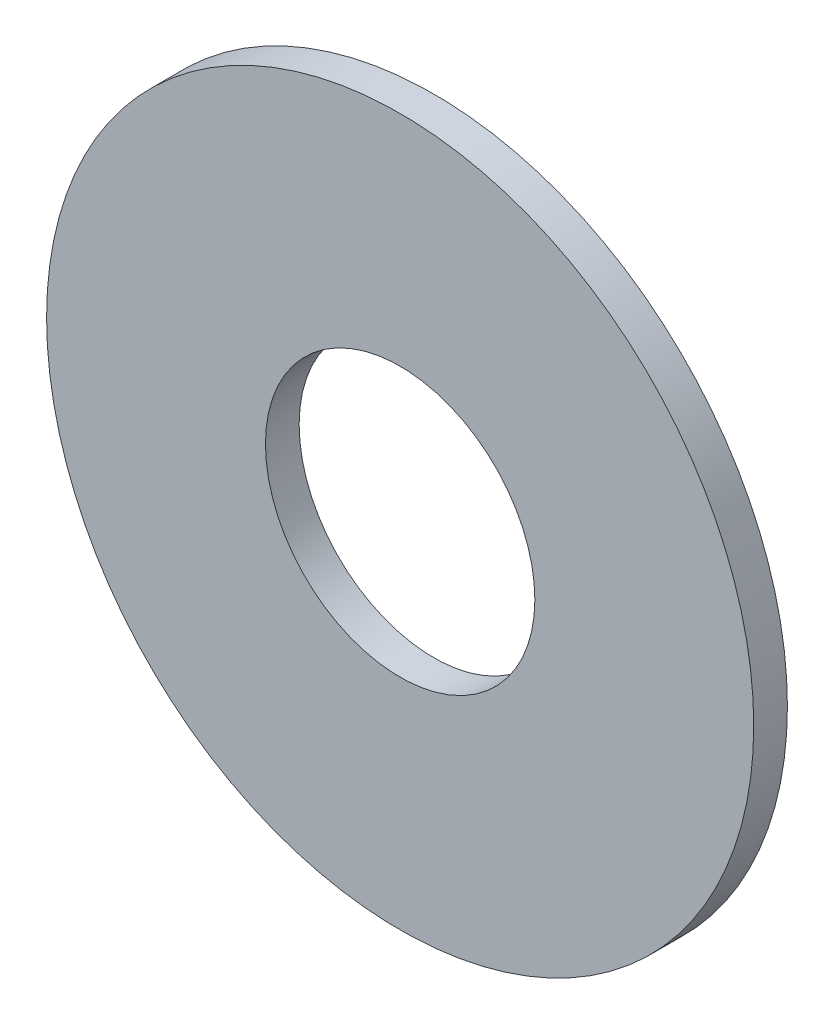
SolidWorks part; units mm, degrees
ref_plane "Alzado" through (0, 0, 0) normal (0, 0, 1) x (1, 0, 0)
ref_plane "Planta" through (0, 0, 0) normal (0, 1, 0) x (1, 0, 0)
ref_plane "Vista lateral" through (0, 0, 0) normal (1, 0, 0) x (0, 0, -1)
sketch "Croquis1" plane through (0, 0, 0) normal (0, 0, 1) x (1, 0, 0)
  circle A0 centre (0, 0) radius 21
  circle A1 centre (0, 0) radius 8
  dimension "D1" = 42
  dimension "D2" = 16
extrude "Saliente-Extruir1" add sketch "Croquis1" along normal blind 2
